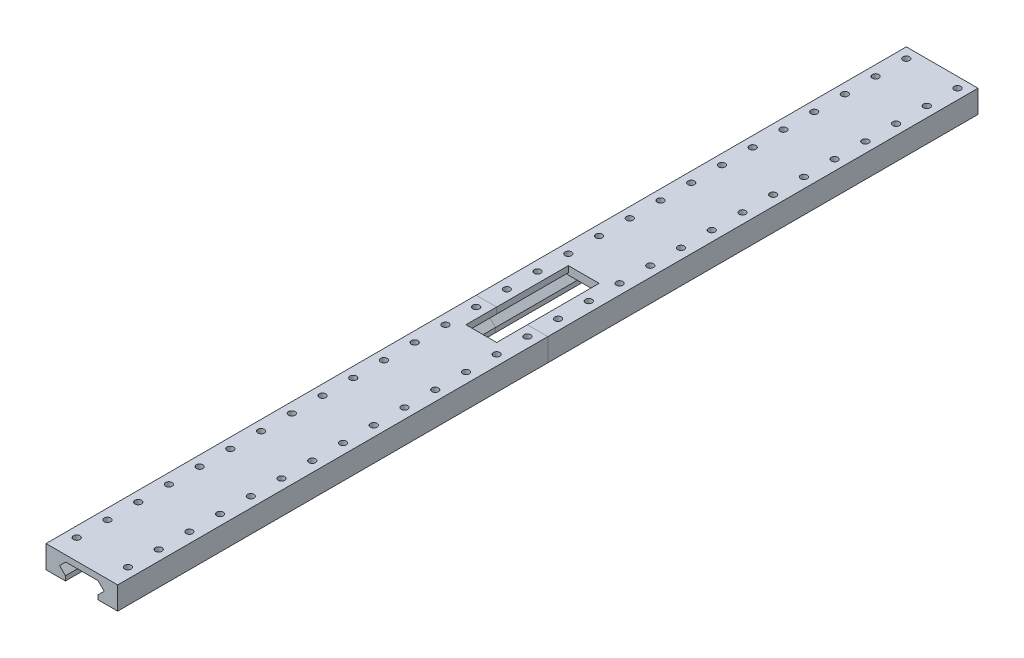
SolidWorks part; units mm, degrees
ref_plane "前视基准面" through (0, 0, 0) normal (0, 0, 1) x (1, 0, 0)
ref_plane "上视基准面" through (0, 0, 0) normal (0, 1, 0) x (1, 0, 0)
ref_plane "右视基准面" through (0, 0, 0) normal (1, 0, 0) x (0, 0, -1)
other "Configuration Table"
sketch "草图1" plane through (0, 0, 0) normal (0, 0, 1) x (1, 0, 0)
  line L0 (0, 0) -> (0, -50000) construction
  line L1 (0, 0) -> (-50000, 0) construction
  line L2 (10, 0) -> (-10, 0)
  line L3 (-10, 0) -> (-10, 2)
  line L4 (-10, 2) -> (-9.3, 2)
  line L5 (-7.8, 3.5) -> (-7.8, 5.8)
  line L6 (-7.8, 5.8) -> (-10.6, 8.6)
  line L7 (-10.6, 8.6) -> (-7.8, 11.4)
  line L8 (-7.8, 11.4) -> (7.8, 11.4)
  line L9 (10.6, 8.6) -> (7.8, 11.4)
  line L10 (7.8, 5.8) -> (10.6, 8.6)
  line L11 (7.8, 3.5) -> (7.8, 5.8)
  line L12 (10, 2) -> (9.3, 2)
  line L13 (10, 0) -> (10, 2)
  line L14 (8, 3.5) -> (8, 5.7172)
  line L15 (8, 5.7172) -> (10.8828, 8.6)
  line L16 (10.8828, 8.6) -> (7.8828, 11.6)
  line L17 (-7.8828, 11.6) -> (7.8828, 11.6)
  line L18 (-10.8828, 8.6) -> (-7.8828, 11.6)
  line L19 (-8, 5.7172) -> (-10.8828, 8.6)
  line L20 (-8, 3.5) -> (-8, 5.7172)
  line L21 (-10.2, 2.2) -> (-9.3, 2.2)
  line L22 (-10.2, -0.2) -> (-10.2, 2.2)
  line L23 (10.2, -0.2) -> (-10.2, -0.2)
  line L24 (10.2, -0.2) -> (10.2, 2.2)
  line L25 (10.2, 2.2) -> (9.3, 2.2)
  line L26 (-8, 3.5) -> (-17.5, 3.5)
  line L27 (-17.5, 3.5) -> (-17.5, 14.6)
  line L28 (-17.5, 14.6) -> (17.5, 14.6)
  line L29 (8, 3.5) -> (17.5, 3.5)
  line L30 (17.5, 3.5) -> (17.5, 14.6)
  arc A0 (-9.3, 2) -> (-7.8, 3.5) centre (-9.3, 3.5) ccw
  arc A1 (9.3, 2) -> (7.8, 3.5) centre (9.3, 3.5) cw
  arc A2 (9.3, 2.2) -> (8, 3.5) centre (9.3, 3.5) cw
  arc A3 (-9.3, 2.2) -> (-8, 3.5) centre (-9.3, 3.5) ccw
  point P21 (0, 11.4)
  point P25 (0, 0)
  point P43 (0, 14.6)
  dimension "D7" = 1.5
  dimension "D1" = 45
  dimension "D2" = 21.2
  dimension "D3" = 15.6
  dimension "D4" = 9.4
  dimension "D5" = 2
  dimension "D6" = 20
  dimension "D9" = 35
  dimension "D10" = 3
  dimension "D8" = 0.2
ref_plane "基准面1" through (0, 0, -150) normal (0, 0, 1) x (1, 0, 0)
sketch "草图2" plane through (0, 0, -150) normal (0, 0, 1) x (1, 0, 0)
  line L0 (-120, 0) -> (-120, -50000) construction
  line L2 (0, 200000) -> (0, -250000) construction
  line L3 (-120, 40) -> (49880, 40) construction
  line L4 (200000, 0) -> (-250000, 0) construction
  point P8 (-120, 40)
  dimension "D1" = 120
  dimension "D2" = 40
sketch3d "3D草图1"
  line L0 (-120, 40, -150) -> (0, 0, 0)
extrude "凸台-拉伸2" add sketch "草图1" along normal blind 420 contours L29 L30 L28 L27 L26 L20 L19 L18 L17 L16 L15 L14
sketch "草图3" plane through (0, 14.6, 0) normal (0, 1, 0) x (1, 0, 0)
  line L0 (0, 0) -> (0, -50000) construction
  line L1 (-12.5, -5) -> (-12.5, -20) construction
  line L2 (-17.5, -420) -> (-17.5, 0) construction
  line L3 (-17.5, 0) -> (17.5, 0) construction
  circle A0 centre (-12.5, -5) radius 1.6
  circle A1 centre (-12.5, -20) radius 1.6
  circle A2 centre (-12.5, -35) radius 1.6
  circle A3 centre (-12.5, -50) radius 1.6
  circle A4 centre (-12.5, -65) radius 1.6
  circle A5 centre (-12.5, -80) radius 1.6
  circle A6 centre (-12.5, -95) radius 1.6
  circle A7 centre (-12.5, -110) radius 1.6
  circle A8 centre (-12.5, -125) radius 1.6
  circle A9 centre (-12.5, -140) radius 1.6
  circle A10 centre (-12.5, -155) radius 1.6
  circle A11 centre (-12.5, -170) radius 1.6
  circle A12 centre (-12.5, -185) radius 1.6
  circle A13 centre (-12.5, -200) radius 1.6
  circle A14 centre (-12.5, -215) radius 1.6
  circle A15 centre (-12.5, -230) radius 1.6
  circle A16 centre (-12.5, -245) radius 1.6
  circle A17 centre (-12.5, -260) radius 1.6
  circle A18 centre (-12.5, -275) radius 1.6
  circle A19 centre (-12.5, -290) radius 1.6
  circle A20 centre (-12.5, -305) radius 1.6
  circle A21 centre (-12.5, -320) radius 1.6
  circle A22 centre (-12.5, -335) radius 1.6
  circle A23 centre (-12.5, -350) radius 1.6
  circle A24 centre (-12.5, -365) radius 1.6
  circle A25 centre (-12.5, -380) radius 1.6
  circle A26 centre (-12.5, -395) radius 1.6
  circle A27 centre (-12.5, -410) radius 1.6
  circle A28 centre (12.5, -410) radius 1.6
  circle A29 centre (12.5, -395) radius 1.6
  circle A30 centre (12.5, -380) radius 1.6
  circle A31 centre (12.5, -365) radius 1.6
  circle A32 centre (12.5, -350) radius 1.6
  circle A33 centre (12.5, -335) radius 1.6
  circle A34 centre (12.5, -320) radius 1.6
  circle A35 centre (12.5, -305) radius 1.6
  circle A36 centre (12.5, -290) radius 1.6
  circle A37 centre (12.5, -275) radius 1.6
  circle A38 centre (12.5, -260) radius 1.6
  circle A39 centre (12.5, -245) radius 1.6
  circle A40 centre (12.5, -230) radius 1.6
  circle A41 centre (12.5, -215) radius 1.6
  circle A42 centre (12.5, -200) radius 1.6
  circle A43 centre (12.5, -185) radius 1.6
  circle A44 centre (12.5, -170) radius 1.6
  circle A45 centre (12.5, -155) radius 1.6
  circle A46 centre (12.5, -140) radius 1.6
  circle A47 centre (12.5, -125) radius 1.6
  circle A48 centre (12.5, -110) radius 1.6
  circle A49 centre (12.5, -95) radius 1.6
  circle A50 centre (12.5, -80) radius 1.6
  circle A51 centre (12.5, -65) radius 1.6
  circle A52 centre (12.5, -50) radius 1.6
  circle A53 centre (12.5, -35) radius 1.6
  circle A54 centre (12.5, -20) radius 1.6
  circle A55 centre (12.5, -5) radius 1.6
  dimension "D3" = 3.2
  dimension "D4" = 5
  dimension "D5" = 5
  dimension "D2" = 15
  dimension "D1" = 28
extrude "切除-拉伸1" cut sketch "草图3" against normal through all
sketch "草图4" plane through (0, 14.6, 0) normal (0, 1, 0) x (1, 0, 0)
  line L0 (0, 0) -> (0, -50000) construction
  line L1 (-17.5, 0) -> (17.5, 0) construction
  line L2 (-7.5, -175) -> (7.5, -175)
  line L3 (-7.5, -175) -> (-7.5, -225)
  line L4 (-7.5, -225) -> (7.5, -225)
  line L5 (7.5, -175) -> (7.5, -225)
  line L6 (-7.5, -175) -> (7.5, -225) construction
  line L7 (-7.5, -225) -> (7.5, -175) construction
  point P3 (0, -200)
  dimension "D1" = 15
  dimension "D2" = 175
  dimension "D3" = 50
extrude "切除-拉伸2" cut sketch "草图4" against normal through all
sketch "草图7" plane through (0, 11.6, 0) normal (0, -1, 0) x (1, 0, 0)
  line L0 (-7.8828, 420) -> (-7.8828, 0) construction
  line L1 (-7.8828, 225) -> (7.8828, 225)
  line L2 (-7.8828, 225) -> (-7.8828, 226.5)
  line L3 (-7.8828, 226.5) -> (7.8828, 226.5)
  line L4 (7.8828, 225) -> (7.8828, 226.5)
  line L5 (7.8828, 420) -> (7.8828, 0) construction
  line L6 (-7.5, 225) -> (7.5, 225) construction
  line L7 (-7.5, 200) -> (49992.5, 200) construction
  line L8 (-7.5, 175) -> (-7.5, 225) construction
  line L9 (7.8828, 175) -> (7.8828, 173.5)
  line L10 (-7.8828, 173.5) -> (7.8828, 173.5)
  line L11 (-7.8828, 175) -> (-7.8828, 173.5)
  line L12 (-7.8828, 175) -> (7.8828, 175)
  point P14 (-7.5, 200)
  dimension "D1" = 1.5
extrude "凸台-拉伸3" add sketch "草图7" along normal blind 1
sketch "草图5" [suppressed] plane through (0, 14.6, 0) normal (0, 1, 0) x (1, 0, 0)
  line L0 (17.5, -420) -> (17.5, 0) construction
  line L1 (-17.5, 0) -> (17.5, 0)
  line L2 (-17.5, 0) -> (-17.5, -210)
  line L3 (-17.5, -210) -> (17.5, -210)
  line L4 (17.5, 0) -> (17.5, -210)
  line L6 (-17.5, -420) -> (17.5, -420)
  line L7 (-17.5, -420) -> (-17.5, -210)
  line L8 (-17.5, -210) -> (17.5, -210)
  line L9 (17.5, -420) -> (17.5, -210)
  dimension "D1" = 210
extrude "切除-拉伸3" [suppressed] cut sketch "草图5" against normal through all contours L4 L1 L2 L3
sketch "草图6" [suppressed] plane through (0, 14.6, 0) normal (0, 1, 0) x (1, 0, 0)
  line L0 (17.5, -420) -> (17.5, 0) construction
  line L1 (-17.5, -420) -> (17.5, -420)
  line L2 (-17.5, -420) -> (-17.5, -210)
  line L3 (-17.5, -210) -> (17.5, -210)
  line L4 (17.5, -420) -> (17.5, -210)
  dimension "D1" = 210
extrude "切除-拉伸4" [suppressed] cut sketch "草图6" against normal through all
ref_plane "基准面2" through (0, 0, 210) normal (0, 0, 1) x (1, 0, 0)
split "分割2" trim tools "基准面2" bodies to split 113 resulting bodies 116 117
